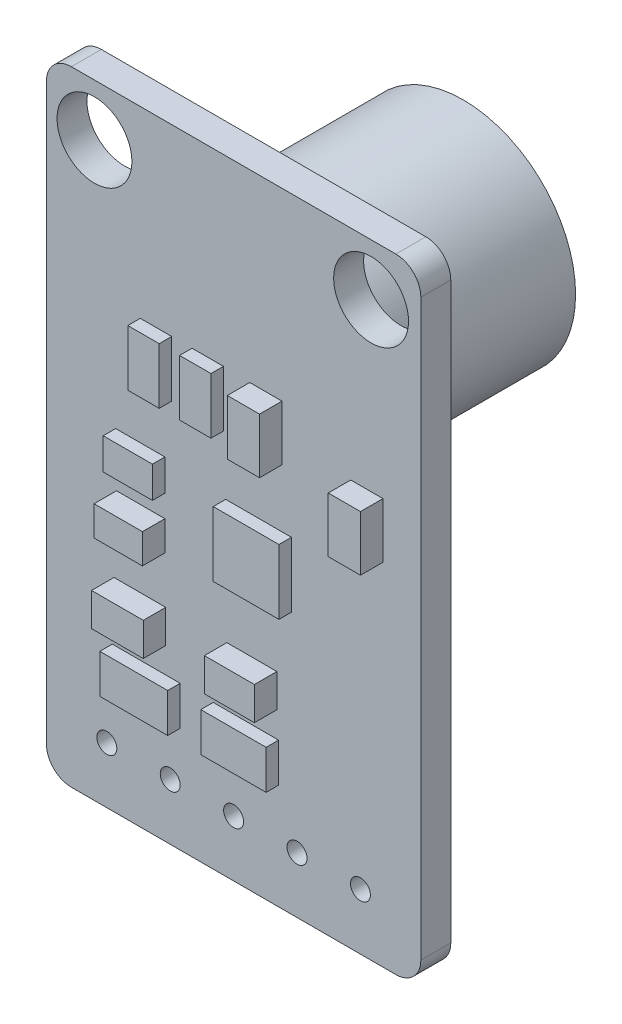
SolidWorks part; units mm, degrees
ref_plane "Front Plane" through (0, 0, 0) normal (0, 0, 1) x (1, 0, 0)
ref_plane "Top Plane" through (0, 0, 0) normal (0, 1, 0) x (1, 0, 0)
ref_plane "Right Plane" through (0, 0, 0) normal (1, 0, 0) x (0, 0, -1)
sketch "Sketch1" plane through (0, 0, 0) normal (0, 0, 1) x (1, 0, 0)
  line L1 (1, 0) -> (14, 0)
  line L2 (0, -1) -> (0, -24)
  line L3 (1, -25) -> (14, -25)
  line L4 (15, -1) -> (15, -24)
  arc A0 (14, -25) -> (15, -24) centre (14, -24) ccw
  arc A1 (1, -25) -> (0, -24) centre (1, -24) cw
  arc A2 (15, -1) -> (14, 0) centre (14, -1) ccw
  arc A3 (0, -1) -> (1, 0) centre (1, -1) cw
  point P8 (15, -25)
  point P13 (15, 0)
  point P16 (0, 0)
  dimension "D3" = 1
  dimension "D1" = 15
  dimension "D2" = 25
extrude "Boss-Extrude1" add sketch "Sketch1" along normal blind 1.2
sketch "Sketch2" plane through (0, 0, 0) normal (0, 0, 1) x (1, 0, 0)
  line L0 (0, -1) -> (0, -24) construction
  circle A0 centre (7.5, -7) radius 4.5
  dimension "D1" = 7.5
extrude "Boss-Extrude2" add sketch "Sketch2" against normal blind 8 contours A0
hole_wizard "Ø3.0mm Dowel Hole1" positions "Sketch3" profile "Sketch4" hole size "Ø3.0" standard "ANSI Metric"
sketch "Sketch3" plane through (0, 0, 0) normal (0, 0, -1) x (-1, 0, 0)
  point P0 (-13.0066, -2.0816)
  point P2 (-1.9254, -2.0816)
sketch "Sketch4" plane through (13.0066, -2.0816, 0) normal (1, 0, 0) x (0, 1, 0)
  line L0 (0, 0) -> (0, 2.9013)
  line L1 (0, 2.9013) -> (1.5, 2)
  line L2 (1.5, 2) -> (1.5, 0)
  line L5 (1.5, 0) -> (0, 0)
  line L10 (0, 2.9013) -> (-1.5, 2) construction
  line L11 (0, -6.35) -> (0, 107.95) construction
  dimension "Hole Dia." = 3
  dimension "Hole Depth" = 2
  dimension "Drill Angle" = 118
hole_wizard "#97 (0.03149606) Diameter Hole1" positions "Sketch14" profile "Sketch15" hole size "#97" standard "ANSI Inch"
sketch "Sketch14" plane through (0, 0, 0) normal (0, 0, -1) x (-1, 0, 0)
  line L0 (-15, -24) -> (-15, -1) construction
  point P0 (-7.5, -22.7485)
  point P2 (-10.04, -22.7485)
  point P4 (-12.58, -22.7485)
  point P6 (-4.96, -22.7485)
  point P8 (-2.42, -22.7485)
  dimension "D1" = 7.5
  dimension "D2" = 2.54
  dimension "D3" = 2.54
  dimension "D4" = 2.54
  dimension "D5" = 2.54
sketch "Sketch15" plane through (7.5, -22.7485, 0) normal (1, 0, 0) x (0, 1, 0)
  line L0 (0, 0) -> (0, 2.2403)
  line L1 (0, 2.2403) -> (0.4, 2)
  line L2 (0.4, 2) -> (0.4, 0)
  line L5 (0.4, 0) -> (0, 0)
  line L10 (0, 2.2403) -> (-0.4, 2) construction
  line L11 (0, -6.35) -> (0, 107.95) construction
  dimension "Hole Dia." = 0.8
  dimension "Hole Depth" = 2
  dimension "Drill Angle" = 118
sketch "Sketch17" plane through (0, 0, 1.2) normal (0, 0, 1) x (1, 0, 0)
  line L1 (7.1832, -11.9193) -> (9.8153, -11.9193)
  line L2 (7.1832, -11.9193) -> (7.1832, -14.518)
  line L3 (7.1832, -14.518) -> (9.8153, -14.518)
  line L4 (9.8153, -11.9193) -> (9.8153, -14.518)
extrude "Boss-Extrude5" add sketch "Sketch17" along normal blind 0.5
sketch "Sketch18" plane through (0, 0, 1.2) normal (0, 0, 1) x (1, 0, 0)
  line L1 (2.6392, -19.2133) -> (5.3585, -19.2133)
  line L2 (2.6392, -19.2133) -> (2.6392, -20.777)
  line L3 (2.6392, -20.777) -> (5.3585, -20.777)
  line L4 (5.3585, -19.2133) -> (5.3585, -20.777)
  line L5 (6.6842, -19.2133) -> (9.3016, -19.2133)
  line L6 (6.6842, -19.2133) -> (6.6842, -20.777)
  line L7 (6.6842, -20.777) -> (9.3016, -20.777)
  line L8 (9.3016, -19.2133) -> (9.3016, -20.777)
extrude "Boss-Extrude6" add sketch "Sketch18" along normal blind 0.5
sketch "Sketch19" plane through (0, 0, 1.2) normal (0, 0, 1) x (1, 0, 0)
  line L1 (2.7072, -16.8679) -> (4.7807, -16.8679)
  line L2 (2.7072, -16.8679) -> (2.7072, -18.1936)
  line L3 (2.7072, -18.1936) -> (4.7807, -18.1936)
  line L4 (4.7807, -16.8679) -> (4.7807, -18.1936)
  line L5 (7.2281, -16.8679) -> (9.2336, -16.8679)
  line L6 (7.2281, -16.8679) -> (7.2281, -18.1936)
  line L7 (7.2281, -18.1936) -> (9.2336, -18.1936)
  line L8 (9.2336, -16.8679) -> (9.2336, -18.1936)
extrude "Boss-Extrude7" add sketch "Sketch19" along normal blind 0.9
sketch "Sketch20" plane through (0, 0, 1.2) normal (0, 0, 1) x (1, 0, 0)
  line L1 (2.7752, -11.6672) -> (4.7467, -11.6672)
  line L2 (2.7752, -11.6672) -> (2.7752, -12.9249)
  line L3 (2.7752, -12.9249) -> (4.7467, -12.9249)
  line L4 (4.7467, -11.6672) -> (4.7467, -12.9249)
  line L5 (3.7609, -7.3503) -> (5.0186, -7.3503)
  line L6 (3.7609, -7.3503) -> (3.7609, -9.5937)
  line L7 (3.7609, -9.5937) -> (5.0186, -9.5937)
  line L8 (5.0186, -7.3503) -> (5.0186, -9.5937)
  line L9 (5.8344, -7.3503) -> (7.0921, -7.3503)
  line L10 (5.8344, -7.3503) -> (5.8344, -9.5937)
  line L11 (5.8344, -9.5937) -> (7.0921, -9.5937)
  line L12 (7.0921, -7.3503) -> (7.0921, -9.5937)
extrude "Boss-Extrude8" add sketch "Sketch20" along normal blind 0.5
sketch "Sketch21" plane through (0, 0, 1.2) normal (0, 0, 1) x (1, 0, 0)
  line L1 (2.8092, -13.8087) -> (4.7467, -13.8087)
  line L2 (2.8092, -13.8087) -> (2.8092, -14.9984)
  line L3 (2.8092, -14.9984) -> (4.7467, -14.9984)
  line L4 (4.7467, -13.8087) -> (4.7467, -14.9984)
  line L5 (8.1458, -7.3843) -> (9.4375, -7.3843)
  line L6 (8.1458, -7.3843) -> (8.1458, -9.5937)
  line L7 (8.1458, -9.5937) -> (9.4375, -9.5937)
  line L8 (9.4375, -7.3843) -> (9.4375, -9.5937)
  line L9 (12.1908, -8.7439) -> (13.4825, -8.7439)
  line L10 (12.1908, -8.7439) -> (12.1908, -10.9534)
  line L11 (12.1908, -10.9534) -> (13.4825, -10.9534)
  line L12 (13.4825, -8.7439) -> (13.4825, -10.9534)
extrude "Boss-Extrude9" add sketch "Sketch21" along normal blind 0.9
